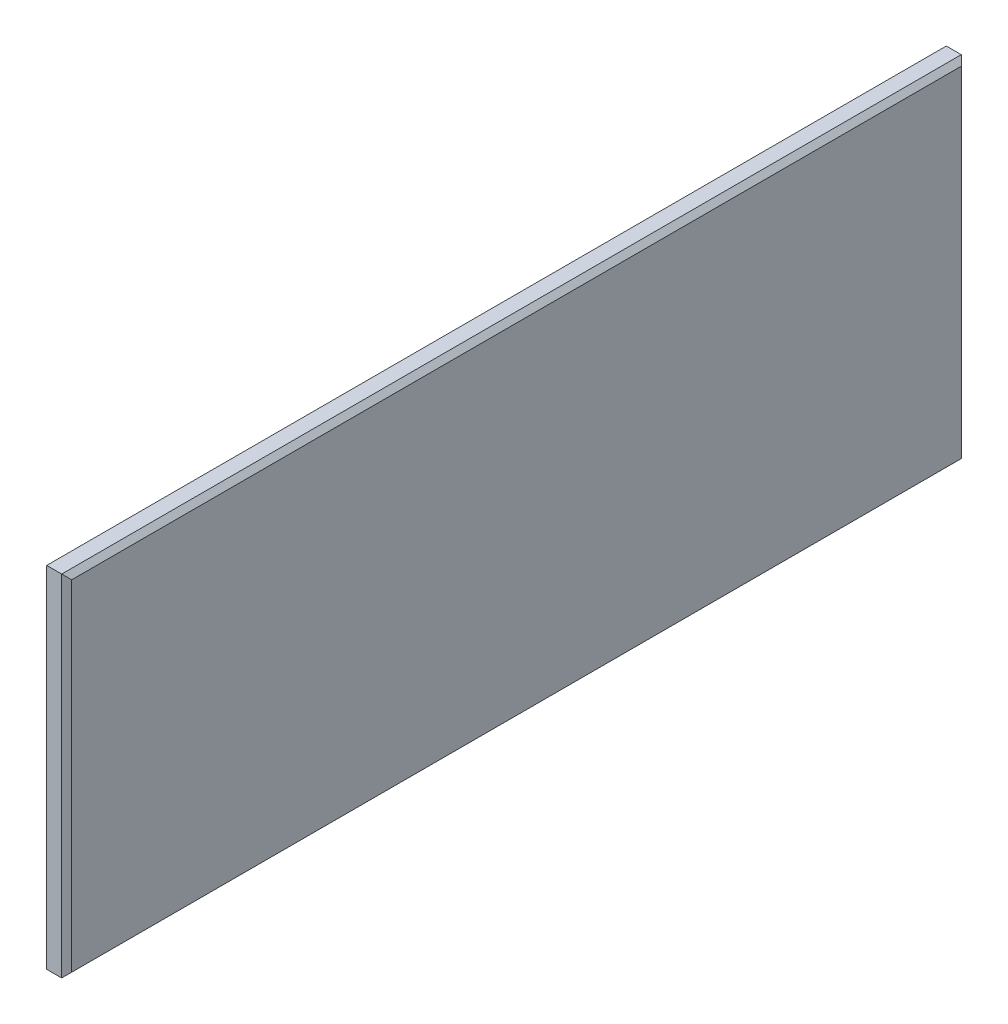
SolidWorks part; units mm, degrees
ref_plane "Front Plane" through (0, 0, 0) normal (0, 0, 1) x (1, 0, 0)
ref_plane "Top Plane" through (0, 0, 0) normal (0, 1, 0) x (1, 0, 0)
ref_plane "Right Plane" through (0, 0, 0) normal (1, 0, 0) x (0, 0, -1)
sketch "Sketch1" plane through (0, 0, 0) normal (0, 1, 0) x (1, 0, 0)
  line L1 (0, 0) -> (5, 0)
  line L2 (0, 0) -> (0, 180)
  line L3 (0, 180) -> (5, 180)
  line L4 (5, 0) -> (5, 180)
  dimension "D1" = 180
  dimension "D2" = 5
extrude "Boss-Extrude1" add sketch "Sketch1" along normal blind 70
chamfer "Chamfer2" distance 1 angle 45 8 edges at (0, 35, -180) (0, 70, -90) (0, 35, 0) (0, 0, -90) (5, 35, 0) (5, 70, -90) (5, 35, -180) (5, 0, -90)
